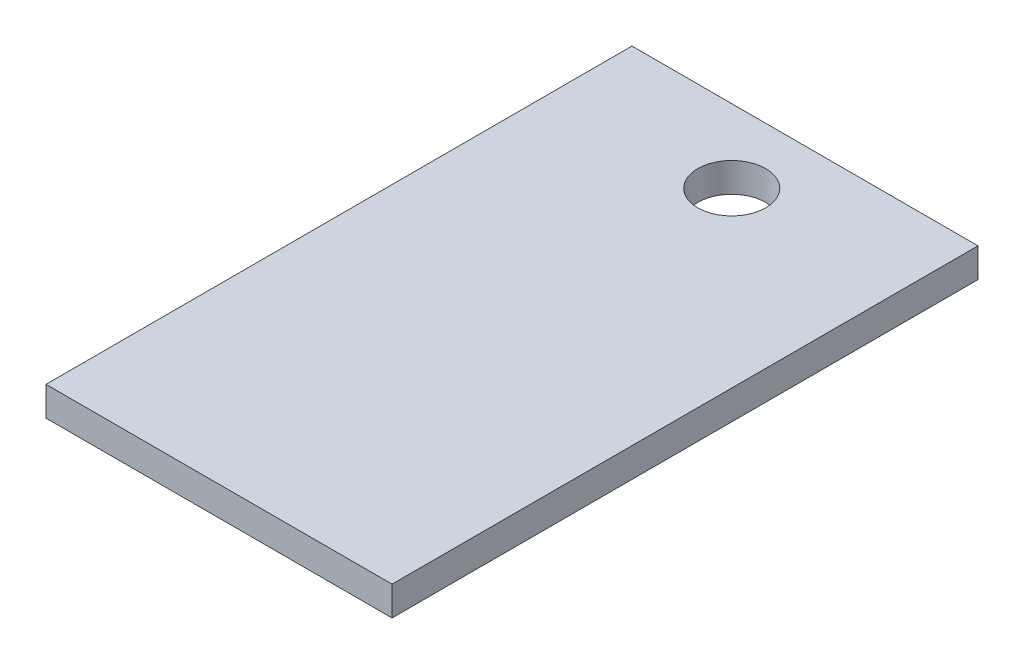
SolidWorks part; units mm, degrees
material "Copper"
ref_plane "Front Plane" through (0, 0, 0) normal (0, 0, 1) x (1, 0, 0)
ref_plane "Top Plane" through (0, 0, 0) normal (0, 1, 0) x (1, 0, 0)
ref_plane "Right Plane" through (0, 0, 0) normal (1, 0, 0) x (0, 0, -1)
sketch "Sketch1" plane through (0, 0, 0) normal (0, 1, 0) x (1, 0, 0)
  line L1 (0, 0) -> (15, 0)
  line L2 (0, 0) -> (0, -25.4)
  line L3 (0, -25.4) -> (15, -25.4)
  line L4 (15, 0) -> (15, -25.4)
  circle A0 centre (7.5, -3.175) radius 1.4732
  point P8 (7.5, 0)
  dimension "D2" = 2.9464
  dimension "D1" = 15
  dimension "D3" = 3.175
  dimension "D4" = 25.4
extrude "Boss-Extrude1" add sketch "Sketch1" along normal blind 1.27
